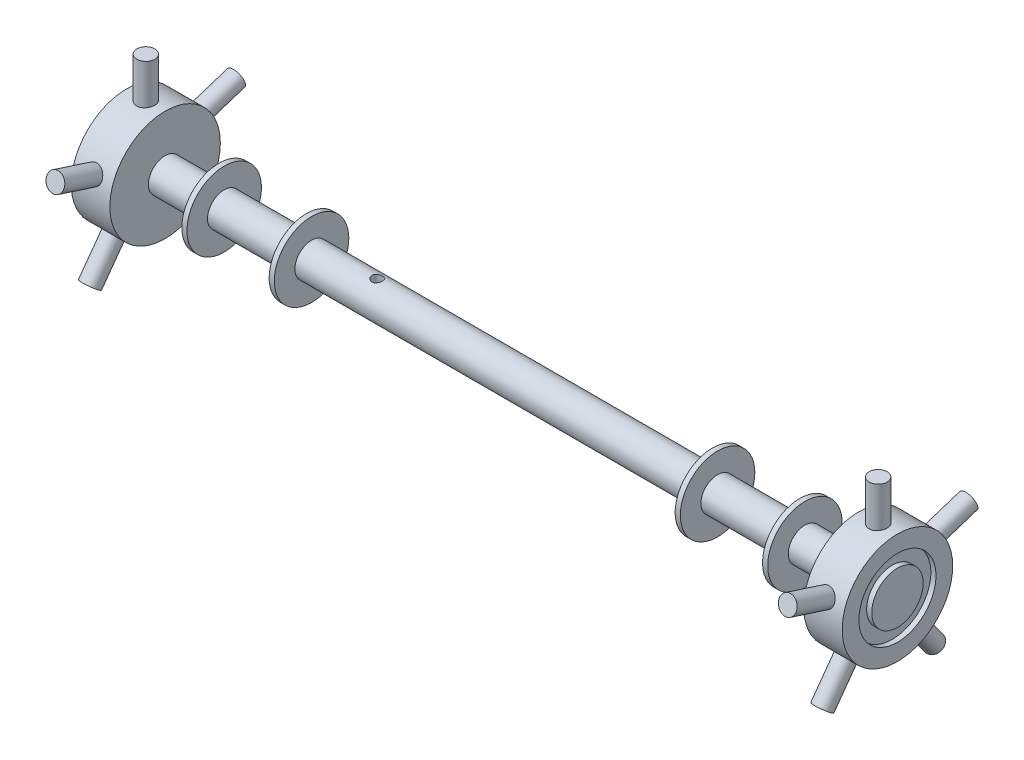
SolidWorks part; units mm, degrees
ref_plane "Front Plane" through (0, 0, 0) normal (0, 0, 1) x (1, 0, 0)
ref_plane "Top Plane" through (0, 0, 0) normal (0, 1, 0) x (1, 0, 0)
ref_plane "Right Plane" through (0, 0, 0) normal (1, 0, 0) x (0, 0, -1)
sketch "Sketch2" plane through (0, 0, 0) normal (1, 0, 0) x (0, 0, -1)
  circle A0 centre (0, 0) radius 8.255
  dimension "D1" = 16.51
extrude "Boss-Extrude1" add sketch "Sketch2" along normal mid plane 381
sketch "Sketch3" plane through (0, 0, 0) normal (0, 0, 1) x (1, 0, 0)
  line L2 (190.5, 27.305) -> (190.5, 8.255)
  line L3 (190.5, 27.305) -> (171.45, 27.305)
  line L4 (171.45, 27.305) -> (171.45, 8.255)
  line L5 (190.5, 8.255) -> (-190.5, 8.255) construction
  line L6 (190.5, 8.255) -> (171.45, 8.255)
  line L7 (-190.5, 8.255) -> (-171.45, 8.255)
  line L8 (-171.45, 8.255) -> (-171.45, 27.305)
  line L9 (-171.45, 27.305) -> (-190.5, 27.305)
  line L10 (-190.5, 27.305) -> (-190.5, 8.255)
  line L11 (-101.6, 8.255) -> (-101.6, 18.415)
  line L12 (-101.6, 18.415) -> (-99.06, 18.415)
  line L13 (-99.06, 18.415) -> (-99.06, 8.255)
  line L14 (-99.06, 8.255) -> (-101.6, 8.255)
  line L15 (0, 0) -> (0, 49.3574) construction
  line L16 (-142.24, 8.255) -> (-142.24, 18.415)
  line L17 (-142.24, 18.415) -> (-144.78, 18.415)
  line L18 (-144.78, 18.415) -> (-144.78, 8.255)
  line L19 (-144.78, 8.255) -> (-142.24, 8.255)
  line L20 (99.06, 8.255) -> (101.6, 8.255)
  line L21 (99.06, 18.415) -> (99.06, 8.255)
  line L22 (101.6, 18.415) -> (99.06, 18.415)
  line L23 (101.6, 8.255) -> (101.6, 18.415)
  line L24 (144.78, 8.255) -> (142.24, 8.255)
  line L25 (142.24, 8.255) -> (142.24, 18.415)
  line L26 (142.24, 18.415) -> (144.78, 18.415)
  line L27 (144.78, 18.415) -> (144.78, 8.255)
  dimension "D1" = 19.05
  dimension "D2" = 19.05
  dimension "D3" = 19.05
  dimension "D4" = 19.05
  dimension "D5" = 2.54
  dimension "D6" = 10.16
  dimension "D7" = 99.06
  dimension "D8" = 2.54
  dimension "D9" = 10.16
  dimension "D10" = 40.64
revolve "Revolve1" add sketch "Sketch3" angle 360 about axis through (190.5, 0, 0) along (-1, 0, 0)
ref_plane "Plane4" through (0, 21.59, 0) normal (0, 1, 0) x (1, 0, 0)
sketch "Sketch5" plane through (0, 21.59, 0) normal (0, 1, 0) x (1, 0, 0)
  line L0 (171.45, 0) -> (144.78, 0) construction
  line L1 (-190.5, 0) -> (-171.45, 0) construction
  line L5 (-190.5, 0) -> (-171.45, 0) construction
  line L6 (-190.5, 27.305) -> (-190.5, -27.305) construction
  line L7 (-171.45, -27.305) -> (-171.45, 27.305) construction
  circle A0 centre (-180.975, 0) radius 4.445
  point P6 (-180.975, 0)
  dimension "D1" = 8.89
sketch "Sketch6" plane through (-190.5, 0, 0) normal (-1, 0, 0) x (0, 0, 1)
  circle A0 centre (0, 0) radius 19.05
  circle A1 centre (0, 0) radius 12.7
  dimension "D1" = 6.35
  dimension "D2" = 38.1
extrude "Cut-Extrude1" cut sketch "Sketch6" against normal blind 2.54
mirror "Mirror2" about plane through (0, 0, 0) normal (1, 0, 0) of "Cut-Extrude1"
extrude "Boss-Extrude3" add sketch "Sketch5" along normal blind 25.4 contours A0
pattern_circular "CirPattern2" count 5 over 360 about axis through (0, 0, 0) along (1, 0, 0) of "Boss-Extrude3"
mirror "Mirror3" about plane through (0, 0, 0) normal (1, 0, 0) of "CirPattern2", "Boss-Extrude3"
sketch "Sketch7" plane through (0, 21.59, 0) normal (0, 1, 0) x (1, 0, 0)
  line L0 (99.06, 0) -> (-99.06, 0) construction
  circle A0 centre (-66.6062, 0) radius 2.54
  dimension "D1" = 5.08
extrude "Cut-Extrude2" cut sketch "Sketch7" against normal through all
